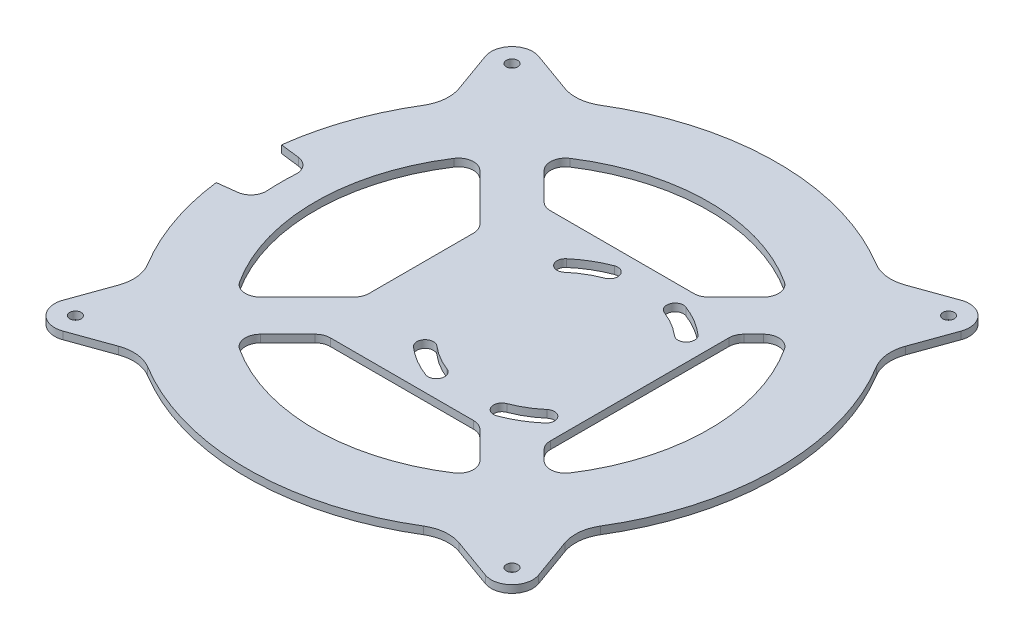
SolidWorks part; units mm, degrees
ref_plane "前视基准面" through (0, 0, 0) normal (0, 0, 1) x (1, 0, 0)
ref_plane "上视基准面" through (0, 0, 0) normal (0, 1, 0) x (1, 0, 0)
ref_plane "右视基准面" through (0, 0, 0) normal (1, 0, 0) x (0, 0, -1)
sketch "草图2" plane through (0, 0, 0) normal (0, 1, 0) x (1, 0, 0)
  line L0 (5.77, 10.5) -> (5.77, -10.5) construction
  line L1 (-4.23, -4.23) -> (4.23, -4.23)
  line L2 (-4.23, -4.23) -> (-4.23, 4.23)
  line L3 (-4.23, 4.23) -> (4.23, 4.23)
  line L4 (4.23, -4.23) -> (4.23, 4.23)
  line L5 (-4.23, -4.23) -> (4.23, 4.23) construction
  line L6 (-4.23, 4.23) -> (4.23, -4.23) construction
  line L7 (14.03, -12.61) -> (-9.97, -12.61)
  line L8 (14.03, -12.61) -> (14.03, 12.61)
  line L9 (14.03, 12.61) -> (-9.97, 12.61)
  line L10 (-9.97, -12.61) -> (-9.97, 12.61)
  line L11 (14.03, -12.61) -> (-9.97, 12.61) construction
  line L12 (14.03, 12.61) -> (-9.97, -12.61) construction
  line L13 (-0.48, -10.5) -> (12.02, -10.5) construction
  line L14 (-0.48, -10.5) -> (-0.48, 10.5) construction
  line L15 (-0.48, 10.5) -> (12.02, 10.5) construction
  line L16 (12.02, -10.5) -> (12.02, 10.5) construction
  line L17 (-0.48, -10.5) -> (12.02, 10.5) construction
  line L18 (-0.48, 10.5) -> (12.02, -10.5) construction
  line L19 (12.02, 0) -> (-0.48, 0) construction
  circle A0 centre (0, 0) radius 3.5427
  circle A1 centre (-0.48, 10.5) radius 1.05
  circle A2 centre (12.02, 10.5) radius 1.05
  circle A3 centre (12.02, -10.5) radius 1.05
  circle A4 centre (-0.48, -10.5) radius 1.05
  point P2 (-20.6918, 12.238)
  point P7 (2.03, 0)
  point P13 (5.77, 0)
  point P25 (6.9083, 0)
  point P26 (0, 0)
  dimension "D1" = 7.0854
  dimension "D7" = 2.1
  dimension "D8" = 10.4
  dimension "D9" = 18.9
  dimension "D2" = 8.46
  dimension "D3" = 8.46
  dimension "D4" = 24
  dimension "D5" = 25.22
  dimension "D6" = 5.74
  dimension "D10" = 8.44
sketch "草图1" plane through (0, 0, 0) normal (0, 1, 0) x (1, 0, 0)
  line L0 (12.02, 0) -> (-0.48, 0) construction
  line L1 (5.77, 10.5) -> (5.77, -10.5) construction
  line L2 (12.02, 0) -> (-0.48, 0) construction
  line L3 (5.77, 10.5) -> (5.77, -10.5) construction
  line L4 (0, 0) -> (28.8146, 28.8146) construction
  line L5 (2.03, 0) -> (35, 0) construction
  line L6 (31.4032, 27.8863) -> (29.4646, 22.4807)
  line L7 (27.8863, 31.4032) -> (22.4807, 29.4646)
  line L8 (27.8863, -31.4032) -> (22.4807, -29.4646)
  line L9 (31.4032, -27.8863) -> (29.4646, -22.4807)
  line L10 (-31.4032, -27.8863) -> (-29.4646, -22.4807)
  line L11 (-27.8863, -31.4032) -> (-22.4807, -29.4646)
  line L12 (-27.8863, 31.4032) -> (-22.4807, 29.4646)
  line L13 (-31.4032, 27.8863) -> (-29.4646, 22.4807)
  line L14 (18.7195, -14.4769) -> (17.4341, -13.1915)
  line L15 (-10.8689, -15.1116) -> (-14.4769, -18.7195)
  line L16 (-9.97, -12.61) -> (-9.97, 12.61) construction
  line L17 (10.8689, -15.1116) -> (14.4769, -18.7195)
  line L18 (16.8484, -11.7773) -> (16.8484, 11.7773)
  line L20 (-11.97, -6.8989) -> (-11.97, 6.8989)
  line L21 (9.4547, 14.5258) -> (-9.4547, 14.5258)
  line L22 (18.7195, 14.4769) -> (17.4341, 13.1915)
  line L23 (10.8689, 15.1116) -> (14.4769, 18.7195)
  line L24 (0, 0) -> (-28.8146, 28.8146) construction
  line L25 (-10.8689, 15.1116) -> (-14.4769, 18.7195)
  line L26 (-12.5558, 8.3131) -> (-18.7195, 14.4769)
  line L27 (0, 0) -> (-26, 0) construction
  line L28 (-0.48, 10.5) -> (12.02, -10.5) construction
  line L29 (5.77, 0) -> (-2.9266, 10.0883) construction
  line L30 (-0.48, 10.5) -> (12.02, -10.5) construction
  line L31 (9.4547, -14.5258) -> (-9.4547, -14.5258)
  line L32 (-12.5558, -8.3131) -> (-18.7195, -14.4769)
  line L33 (0, 0) -> (-34.7329, 4.3159) construction
  line L34 (-32.1908, 4) -> (-34.7329, 4.3159)
  line L35 (-34.7329, 4.3159) -> (-25.8016, 3.2061) construction
  line L36 (-32.1908, -4) -> (-34.7329, -4.3159)
  circle A0 centre (0, 0) radius 34 construction
  circle A1 centre (0, 0) radius 27 construction
  circle A2 centre (-0.48, 10.5) radius 1.1 construction
  circle A6 centre (0, 0) radius 35 construction
  circle A7 centre (28.8146, 28.8146) radius 0.75
  arc A8 (27.8863, 31.4032) -> (31.4032, 27.8863) centre (28.8146, 28.8146) cw
  arc A9 (29.8997, 18.1937) -> (35, 0) centre (0, 0) cw
  arc A10 (29.8997, 18.1937) -> (29.4646, 22.4807) centre (34.171, 20.7928) cw
  arc A11 (18.1937, 29.8997) -> (0, 35) centre (0, 0) ccw
  arc A12 (18.1937, 29.8997) -> (22.4807, 29.4646) centre (20.7928, 34.171) ccw
  arc A13 (18.1937, -29.8997) -> (0, -35) centre (0, 0) cw
  circle A14 centre (28.8146, -28.8146) radius 0.75
  arc A15 (31.4032, -27.8863) -> (27.8863, -31.4032) centre (28.8146, -28.8146) cw
  arc A16 (18.1937, -29.8997) -> (22.4807, -29.4646) centre (20.7928, -34.171) cw
  arc A17 (29.8997, -18.1937) -> (35, 0) centre (0, 0) ccw
  arc A18 (29.8997, -18.1937) -> (29.4646, -22.4807) centre (34.171, -20.7928) ccw
  arc A19 (-29.8997, -18.1937) -> (-35, 0) centre (0, 0) cw
  circle A20 centre (-28.8146, -28.8146) radius 0.75
  arc A21 (-27.8863, -31.4032) -> (-31.4032, -27.8863) centre (-28.8146, -28.8146) cw
  arc A22 (-29.8997, -18.1937) -> (-29.4646, -22.4807) centre (-34.171, -20.7928) cw
  arc A23 (-18.1937, -29.8997) -> (0, -35) centre (0, 0) ccw
  arc A24 (-18.1937, -29.8997) -> (-22.4807, -29.4646) centre (-20.7928, -34.171) ccw
  arc A25 (-18.1937, 29.8997) -> (0, 35) centre (0, 0) cw
  circle A26 centre (-28.8146, 28.8146) radius 0.75
  arc A27 (-31.4032, 27.8863) -> (-27.8863, 31.4032) centre (-28.8146, 28.8146) cw
  arc A28 (-18.1937, 29.8997) -> (-22.4807, 29.4646) centre (-20.7928, 34.171) cw
  arc A29 (-29.8997, 18.1937) -> (-35, 0) centre (0, 0) ccw
  arc A30 (-29.8997, 18.1937) -> (-29.4646, 22.4807) centre (-34.171, 20.7928) ccw
  circle A31 centre (0, 0) radius 26 construction
  arc A32 (21.8115, -14.1512) -> (21.8115, 14.1512) centre (0, 0) ccw
  arc A33 (-14.1512, 21.8115) -> (14.1512, 21.8115) centre (0, 0) cw
  arc A34 (-21.8115, 14.1512) -> (-21.8115, -14.1512) centre (0, 0) ccw
  arc A35 (1.0483, 12.4543) -> (-2.9266, 10.0883) centre (5.77, 0) ccw
  arc A36 (1.8282, 10.3972) -> (-1.4901, 8.422) centre (5.77, 0) ccw
  arc A37 (-2.9266, 10.0883) -> (-1.4901, 8.422) centre (-2.2084, 9.2552) ccw
  arc A38 (1.0483, 12.4543) -> (1.8282, 10.3972) centre (1.4383, 11.4258) cw
  arc A39 (10.4917, 12.4543) -> (9.7118, 10.3972) centre (10.1017, 11.4258) ccw
  arc A40 (10.4917, 12.4543) -> (14.4666, 10.0883) centre (5.77, 0) cw
  arc A41 (14.4666, 10.0883) -> (13.0301, 8.422) centre (13.7484, 9.2552) cw
  arc A42 (9.7118, 10.3972) -> (13.0301, 8.422) centre (5.77, 0) cw
  arc A43 (1.0483, -12.4543) -> (1.8282, -10.3972) centre (1.4383, -11.4258) ccw
  arc A44 (1.0483, -12.4543) -> (-2.9266, -10.0883) centre (5.77, 0) cw
  arc A45 (-2.9266, -10.0883) -> (-1.4901, -8.422) centre (-2.2084, -9.2552) cw
  arc A46 (1.8282, -10.3972) -> (-1.4901, -8.422) centre (5.77, 0) cw
  arc A47 (10.4917, -12.4543) -> (14.4666, -10.0883) centre (5.77, 0) ccw
  arc A48 (14.4666, -10.0883) -> (13.0301, -8.422) centre (13.7484, -9.2552) ccw
  arc A49 (9.7118, -10.3972) -> (13.0301, -8.422) centre (5.77, 0) ccw
  arc A50 (10.4917, -12.4543) -> (9.7118, -10.3972) centre (10.1017, -11.4258) cw
  arc A51 (-21.8115, 14.1512) -> (-18.7195, 14.4769) centre (-20.1337, 13.0627) cw
  arc A52 (-14.1512, 21.8115) -> (-14.4769, 18.7195) centre (-13.0627, 20.1337) ccw
  arc A53 (18.7195, 14.4769) -> (21.8115, 14.1512) centre (20.1337, 13.0627) cw
  arc A54 (14.1512, 21.8115) -> (14.4769, 18.7195) centre (13.0627, 20.1337) cw
  arc A55 (17.4341, 13.1915) -> (16.8484, 11.7773) centre (18.8484, 11.7773) ccw
  arc A56 (10.8689, 15.1116) -> (9.4547, 14.5258) centre (9.4547, 16.5258) cw
  arc A57 (-10.8689, 15.1116) -> (-9.4547, 14.5258) centre (-9.4547, 16.5258) ccw
  arc A58 (-12.5558, 8.3131) -> (-11.97, 6.8989) centre (-13.97, 6.8989) cw
  arc A59 (17.4341, -13.1915) -> (16.8484, -11.7773) centre (18.8484, -11.7773) cw
  arc A60 (18.7195, -14.4769) -> (21.8115, -14.1512) centre (20.1337, -13.0627) ccw
  arc A61 (-14.1512, -21.8115) -> (-14.4769, -18.7195) centre (-13.0627, -20.1337) cw
  arc A62 (-14.1512, -21.8115) -> (14.1512, -21.8115) centre (0, 0) ccw
  arc A63 (14.1512, -21.8115) -> (14.4769, -18.7195) centre (13.0627, -20.1337) ccw
  arc A64 (10.8689, -15.1116) -> (9.4547, -14.5258) centre (9.4547, -16.5258) ccw
  arc A65 (-10.8689, -15.1116) -> (-9.4547, -14.5258) centre (-9.4547, -16.5258) cw
  arc A66 (-12.5558, -8.3131) -> (-11.97, -6.8989) centre (-13.97, -6.8989) ccw
  arc A67 (-21.8115, -14.1512) -> (-18.7195, -14.4769) centre (-20.1337, -13.0627) ccw
  arc A68 (-30.4413, -1.8912) -> (-30.4413, 1.8912) centre (0, 0) cw
  arc A69 (-30.4413, 1.8912) -> (-32.1908, 4) centre (-32.4375, 2.0153) ccw
  arc A70 (-30.4413, -1.8912) -> (-32.1908, -4) centre (-32.4375, -2.0153) cw
  point P12 (-1.0426, 11.4452)
  point P16 (0, 0)
  point P30 (28.625, 20.1397)
  point P68 (-16.1407, 20.3833)
  point P72 (0, 0)
  point P82 (-25.7713, 3.4406)
  point P87 (-29.7531, 6.7085)
  point P93 (-30.2672, 3.761)
  point P97 (-30.2672, 3.761)
  point P126 (-20.3833, 16.1407)
  point P139 (16.8484, 0)
  point P156 (-11.97, 0)
  dimension "D1" = 68
  dimension "D2" = 7
  dimension "D3" = 2.2
  dimension "D4" = 1
  dimension "D5" = 1.5
  dimension "D7" = 5
  dimension "D8" = 2
  dimension "D10" = 5
  dimension "D12" = 1
  dimension "D21" = 2
  dimension "D6" = 2
  dimension "D9" = 6
  dimension "D13" = 3
  dimension "D14" = 3
  dimension "D15" = 3
  dimension "D16" = 3
  dimension "D17" = 10
  dimension "D18" = 2
  dimension "D19" = 2
  dimension "D20" = 2
  dimension "D22" = 8
  dimension "D11" = 4
extrude "凸台-拉伸1" add sketch "草图1" along normal blind 1 contours A30 A29 A19 A22 L10 A21 L11 A24 A23 A13 A16 L8 A15 L9 A18 A17 A9 A10 L6 A8 L7 A12 A11 A25 A28 L12 A27 L13 A67 A34 A51 L26 A58 L20 A66 L32 A60 L14 A59 L18 A55 L22 A53 A32 A57 L25 A52 A33
